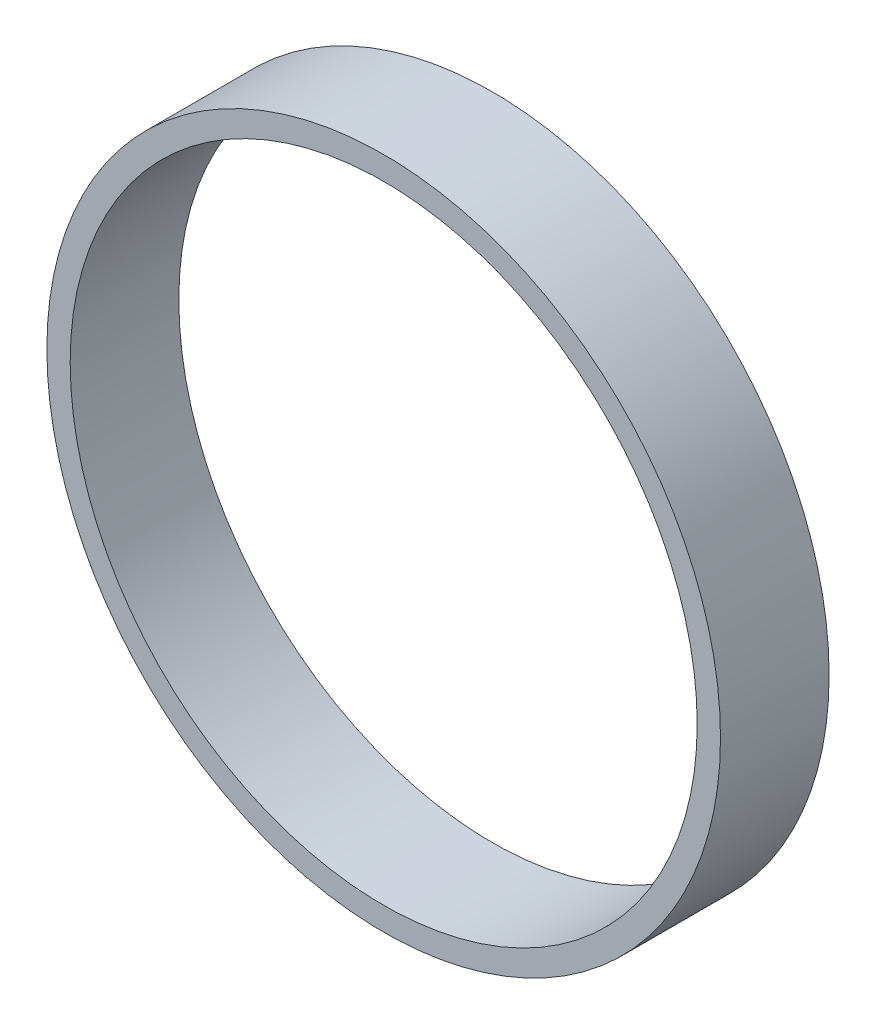
SolidWorks part; units mm, degrees
ref_plane "Front Plane" through (0, 0, 0) normal (0, 0, 1) x (1, 0, 0)
ref_plane "Top Plane" through (0, 0, 0) normal (0, 1, 0) x (1, 0, 0)
ref_plane "Right Plane" through (0, 0, 0) normal (1, 0, 0) x (0, 0, -1)
sketch "Sketch1" plane through (0, 0, 0) normal (0, 0, 1) x (1, 0, 0)
  circle A0 centre (0, 0) radius 31.75
  circle A1 centre (0, 0) radius 34.11
  dimension "D1" = 63.5
  dimension "D2" = 68.22
extrude "Boss-Extrude1" add sketch "Sketch1" along normal blind 11
